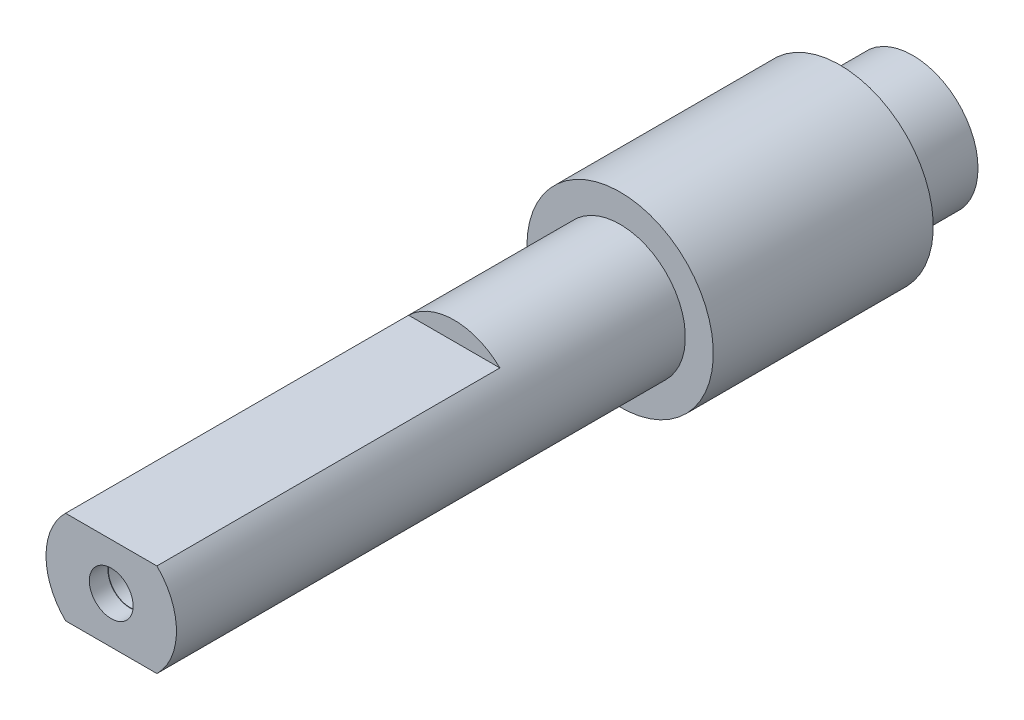
SolidWorks part; units mm, degrees
ref_plane "前视基准面" through (0, 0, 0) normal (0, 0, 1) x (1, 0, 0)
ref_plane "上视基准面" through (0, 0, 0) normal (0, 1, 0) x (1, 0, 0)
ref_plane "右视基准面" through (0, 0, 0) normal (1, 0, 0) x (0, 0, -1)
sketch "草图1" plane through (0, 0, 0) normal (0, 0, 1) x (1, 0, 0)
  circle A0 centre (0, 0) radius 3.5
  dimension "D1" = 7
extrude "凸台-拉伸1" add sketch "草图1" along normal blind 43
sketch "草图2" plane through (0, 0, 43) normal (0, 0, 1) x (1, 0, 0)
  line L1 (-5.2969, 2.5) -> (5.2969, 2.5)
  line L2 (-5.2969, 2.5) -> (-5.2969, -2.5)
  line L3 (-5.2969, -2.5) -> (5.2969, -2.5)
  line L4 (5.2969, 2.5) -> (5.2969, -2.5)
  line L5 (-5.2969, 2.5) -> (5.2969, -2.5) construction
  line L6 (-5.2969, -2.5) -> (5.2969, 2.5) construction
  point P0 (0, 0)
  dimension "D1" = 5
extrude "切除-拉伸1" cut sketch "草图2" against normal blind 18.4 flip side to cut
sketch "草图3" plane through (0, 0, 43) normal (0, 0, 1) x (1, 0, 0)
  circle A0 centre (0, 0) radius 1.175
  dimension "D1" = 2.35
sketch "草图5" plane through (0, 0, 0) normal (0, 0, -1) x (-1, 0, 0)
  circle A0 centre (0, 0) radius 5
  dimension "D1" = 10
extrude "凸台-拉伸2" add sketch "草图5" against normal blind 11.8 from offset 3.9 offset against normal yes
extrude "切除-拉伸2" cut sketch "草图3" against normal blind 1 contours A0
sketch "草图6" plane through (0, 0, 42) normal (0, 0, 1) x (1, 0, 0)
  circle A0 centre (0, 0) radius 1.15
  dimension "D1" = 2.3
extrude "切除-拉伸3" cut sketch "草图6" against normal blind 6
